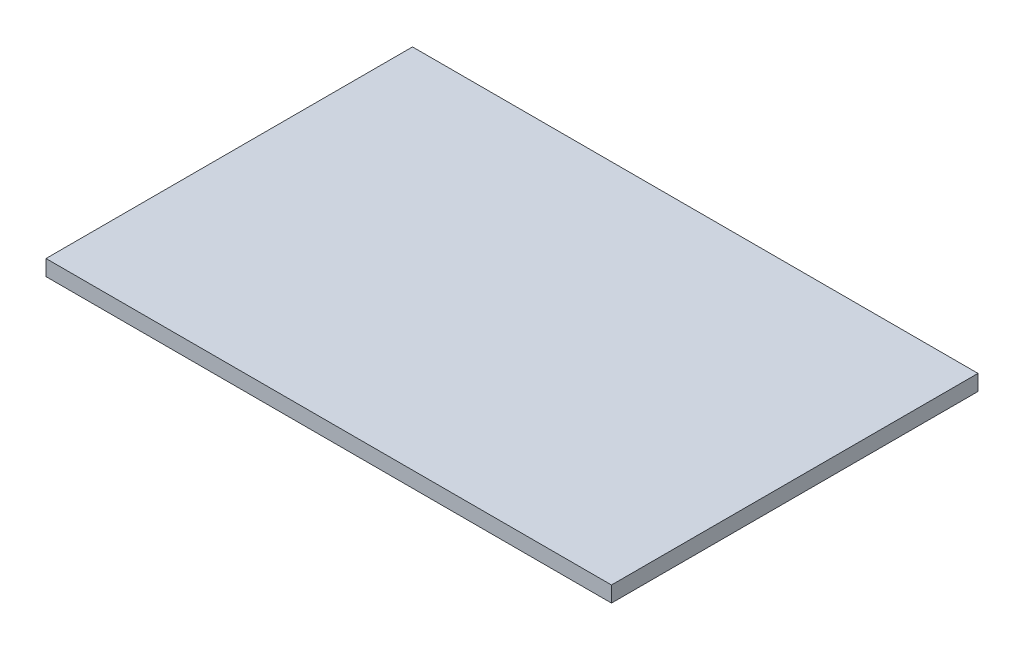
SolidWorks part; units mm, degrees
ref_plane "Front Plane" through (0, 0, 0) normal (0, 0, 1) x (1, 0, 0)
ref_plane "Top Plane" through (0, 0, 0) normal (0, 1, 0) x (1, 0, 0)
ref_plane "Right Plane" through (0, 0, 0) normal (1, 0, 0) x (0, 0, -1)
sketch "Sketch1" plane through (0, 0, 0) normal (0, 1, 0) x (1, 0, 0)
  line L1 (-54, -35) -> (54, -35)
  line L2 (-54, -35) -> (-54, 35)
  line L3 (-54, 35) -> (54, 35)
  line L4 (54, -35) -> (54, 35)
  line L5 (-54, -35) -> (54, 35) construction
  line L6 (-54, 35) -> (54, -35) construction
  point P0 (0, 0)
  dimension "D1" = 108
  dimension "D2" = 70
extrude "Boss-Extrude1" add sketch "Sketch1" along normal blind 3
equation "\"T\"= 3mm"
equation "\"D1@Boss-Extrude1\"=\"T\""
